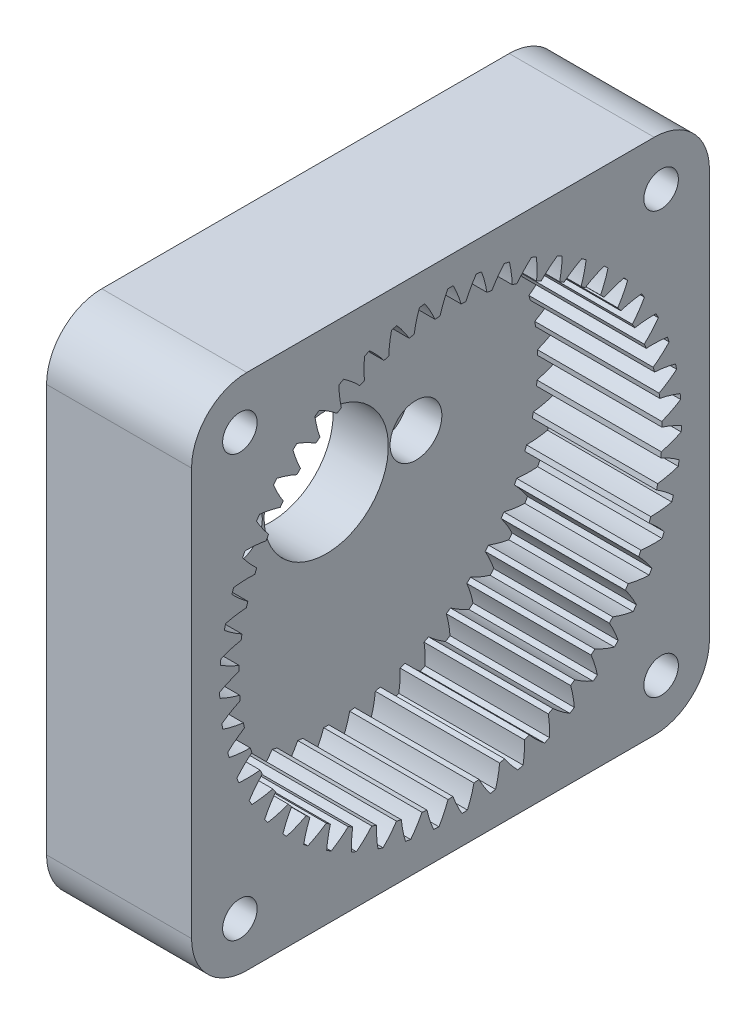
SolidWorks part; units mm, degrees
ref_plane "Plane1" through (0, 0, 0) normal (0, 0, 1) x (1, 0, 0)
ref_plane "Plane2" through (0, 0, 0) normal (0, 1, 0) x (1, 0, 0)
ref_plane "Plane3" through (0, 0, 0) normal (1, 0, 0) x (0, 0, -1)
sketch "HoldingSke" plane through (0, 0, 0) normal (0, 1, 0) x (1, 0, 0)
  line L0 (0, 0) -> (0.5035, -0.6217)
  line L1 (-15, 0) -> (100, 0) construction
  line L2 (0, 0) -> (-2.1039, 2.3779)
  line L3 (0, 0) -> (-11.863, 4.5341)
  line L4 (0, 0) -> (5.4348, 6.7114)
  line L5 (0, 0) -> (-23.7986, -8.8762)
  line L6 (0, 0) -> (-10.5278, -7.1032)
  line L7 (-2.1039, 2.3779) -> (3.3635, 27.1825)
  line L8 (-76.2, 3.6279) -> (-54.61, 3.6279)
  line L9 (-71.009, 38.7566) -> (-53.1078, 45.2721)
  line L10 (-76.2, 71.12) -> (104.1128, 71.12)
  line L11 (0, 0) -> (-12, 0)
  line L12 (-76.2, 101.6) -> (-76.155, 101.6)
  line L13 (24.9733, 27.94) -> (52.9518, 28.4284)
  line L14 (24.9733, 27.94) -> (24.9743, 27.94)
  line L15 (24.9733, 27.94) -> (100.4006, 29.5858)
  circle A0 centre (0, 0) radius 37.5
  circle A1 centre (0, 0) radius 12.7
  circle A2 centre (0, 0) radius 12.7
  dimension "MHD" = 25.4
  dimension "Hub_dia" = 25.4
  dimension "Diameter" = 75
  dimension "Num_teeth" = 51
  dimension "Pitch" = 0.8
  dimension "Overall_len" = 25.4
  dimension "Show_teeth" = 51
  dimension "Thickness" = 12.7
  dimension "OAL" = 25.4001
  dimension "T_dim" = 21.59
  dimension "Ap" = 20
  dimension "H" = 19.05
  dimension "Pitch_radius" = 180.3128
  dimension "Width" = 12
  dimension "Backlash" = 0.045
  dimension "Addendum_fac" = 1
  dimension "Dedendum_fac" = 1.25
  dimension "Clearance_fac" = 0.25
  dimension "Dedendum_add" = 0.001
  dimension "Module" = 1.25
sketch "BasProSke" plane through (0, 0, 0) normal (0, 1, 0) x (1, 0, 0)
  line L0 (-10, 0) -> (60, 0) construction
  line L1 (0, 30.625) -> (0, 37.5)
  line L2 (0, 30.625) -> (12, 30.625)
  line L3 (12, 30.625) -> (12, 37.5)
  line L4 (12, 37.5) -> (0, 37.5)
  dimension "Diameter" = 75
  dimension "Thickness" = 12
  dimension "Inside_diameter" = 61.25
revolve "Base-Revolve" add sketch "BasProSke" angle 360 about L0
sketch "TooCutSke" plane through (0, 0, 0) normal (1, 0, 0) x (0, 0, -1)
  line L3 (1.0941, 31.8562) -> (1.0941, 53.6633) construction
  line L4 (0, 0) -> (0, 59.563) construction
  line L5 (0, 0) -> (-4.2063, 68.1979) construction
  line L6 (-13.79, 26.1581) -> (36.1115, 29.2359) construction
  circle A0 centre (0, 0) radius 31.875 construction
  circle A1 centre (0, 0) radius 33.4385 construction
  circle A2 centre (0, 0) radius 26.9574 construction
  circle A3 centre (0, 0) radius 30.5996 construction
  arc A4 (1.5271, 30.5615) -> (0.3886, 33.4362) centre (-13.79, 26.1581) ccw
  arc A5 (1.5271, 30.5615) -> (-1.5271, 30.5615) centre (0, 0) ccw
  arc A6 (0.3886, 33.4362) -> (-0.3886, 33.4362) centre (0, 0) ccw
  arc A7 (-0.3886, 33.4362) -> (-1.5271, 30.5615) centre (13.79, 26.1581) ccw
  dimension "Pitch_dia" = 63.75
  dimension "Base_dia" = 53.9149
  dimension "Root_dia" = 66.877
  dimension "Overcut_dia" = 61.1992
  dimension "Flank_rad" = 15.9375
  dimension "Half_ang" = 3.529
  dimension "Half_CT" = 1.0941
extrude "ToothCut" cut sketch "TooCutSke" along normal through all
fillet "Breaks" [suppressed] radius 0.125
fillet "RootFillets" [suppressed] radius 0.3135
pattern_circular "TeethCuts" count 51 every 7.059 about axis through (-10, 0, 0) along (1, 0, 0) of "RootFillets", "Breaks", "ToothCut"
sketch "Sketch1" plane through (12, 0, 0) normal (1, 0, 0) x (0, 0, -1)
  line L1 (-37.5, 37.5) -> (37.5, 37.5)
  line L2 (-37.5, 37.5) -> (-37.5, -37.5)
  line L3 (-37.5, -37.5) -> (37.5, -37.5)
  line L4 (37.5, 37.5) -> (37.5, -37.5)
  circle A0 centre (0, 0) radius 37.5 construction
  circle A1 centre (0, 0) radius 37.5
extrude "Boss-Extrude1" add sketch "Sketch1" against normal up to surface (12 mm away) contours A1 L1 L2 | A1 L4 L1 | A1 L3 L4 | A1 L2 L3 up to face at (0, 0, 37.5)
sketch "Sketch2" plane through (0, 0, 0) normal (-1, 0, 0) x (0, 0, 1)
  line L1 (-37.5, 37.5) -> (37.5, 37.5)
  line L2 (-37.5, 37.5) -> (-37.5, -37.5)
  line L3 (-37.5, -37.5) -> (37.5, -37.5)
  line L4 (37.5, 37.5) -> (37.5, -37.5)
extrude "Boss-Extrude2" add sketch "Sketch2" along normal blind 3
sketch "Sketch3" plane through (-3, 0, 0) normal (-1, 0, 0) x (0, 0, 1)
  line L0 (0, 37.5) -> (0, -37.5)
  line L1 (37.5, 37.5) -> (-37.5, 37.5) construction
  line L2 (-37.5, -37.5) -> (37.5, -37.5) construction
  circle A0 centre (0, 0) radius 9
  dimension "D1" = 18
extrude "Cut-Extrude1" cut sketch "Sketch3" against normal through all contours L0 A0 | L0 A0
sketch "Sketch4" plane through (12, 0, 0) normal (1, 0, 0) x (0, 0, -1)
  line L1 (-37.5, 37.5) -> (37.5, 37.5)
  line L2 (-37.5, 37.5) -> (-37.5, -37.5)
  line L3 (-37.5, -37.5) -> (37.5, -37.5)
  line L4 (37.5, 37.5) -> (37.5, -37.5)
  arc A204 (3.7232, 33.2306) -> (2.2506, 30.5422) centre (16.9, 24.2652) ccw
  arc A205 (4.4946, 33.1351) -> (3.7232, 33.2306) centre (0, 0) ccw
  arc A206 (5.267, 30.1687) -> (4.4946, 33.1351) centre (-10.4709, 27.6545) ccw
  arc A207 (5.9868, 30.0341) -> (5.267, 30.1687) centre (0, 0) ccw
  arc A208 (7.7787, 32.5212) -> (5.9868, 30.0341) centre (19.7538, 22.0045) ccw
  arc A209 (8.5324, 32.3316) -> (7.7787, 32.5212) centre (0, 0) ccw
  arc A210 (8.9345, 29.2928) -> (8.5324, 32.3316) centre (-6.9932, 28.7316) ccw
  arc A211 (9.6323, 29.0708) -> (8.9345, 29.2928) centre (0, 0) ccw
  arc A212 (11.7162, 31.3188) -> (9.6323, 29.0708) centre (22.3082, 19.4102) ccw
  arc A213 (12.4409, 31.038) -> (11.7162, 31.3188) centre (0, 0) ccw
  arc A214 (12.4665, 27.9728) -> (12.4409, 31.038) centre (-3.4094, 29.3732) ccw
  arc A215 (13.1318, 27.6667) -> (12.4665, 27.9728) centre (0, 0) ccw
  arc A216 (15.4761, 29.6416) -> (13.1318, 27.6667) centre (24.5244, 16.5217) ccw
  arc A217 (16.1609, 29.2739) -> (15.4761, 29.6416) centre (0, 0) ccw
  arc A218 (15.8095, 26.2288) -> (16.1609, 29.2739) centre (0.2261, 29.5696) ccw
  arc A219 (16.4321, 25.8433) -> (15.8095, 26.2288) centre (0, 0) ccw
  arc A220 (19.0014, 27.5151) -> (16.4321, 25.8433) centre (26.3688, 13.3827) ccw
  arc A221 (19.6358, 27.066) -> (19.0014, 27.5151) centre (0, 0) ccw
  arc A222 (18.9129, 24.0872) -> (19.6358, 27.066) centre (3.8581, 29.3177) ccw
  arc A223 (19.4834, 23.6281) -> (18.9129, 24.0872) centre (0, 0) ccw
  arc A224 (22.2387, 24.9715) -> (19.4834, 23.6281) centre (27.8135, 10.0408) ccw
  arc A225 (22.813, 24.4479) -> (22.2387, 24.9715) centre (0, 0) ccw
  arc A226 (21.7296, 21.5804) -> (22.813, 24.4479) centre (7.4317, 28.6213) ccw
  arc A227 (22.2394, 21.0547) -> (21.7296, 21.5804) centre (0, 0) ccw
  arc A228 (25.1388, 22.0494) -> (22.2394, 21.0547) centre (28.8366, 6.5468) ccw
  arc A229 (25.6445, 21.4591) -> (25.1388, 22.0494) centre (0, 0) ccw
  arc A230 (24.2169, 18.7466) -> (25.6445, 21.4591) centre (10.8926, 27.4911) ccw
  arc A231 (24.6582, 18.1622) -> (24.2169, 18.7466) centre (0, 0) ccw
  arc A232 (27.6579, 18.793) -> (24.6582, 18.1622) centre (29.4226, 2.9535) ccw
  arc A233 (28.0872, 18.145) -> (27.6579, 18.793) centre (0, 0) ccw
  arc A234 (26.3371, 15.6285) -> (28.0872, 18.145) centre (14.1884, 25.9442) ccw
  arc A235 (26.7032, 14.9943) -> (26.3371, 15.6285) centre (0, 0) ccw
  arc A236 (29.7577, 15.2517) -> (26.7032, 14.9943) centre (29.5625, -0.6846) ccw
  arc A237 (30.1041, 14.5559) -> (29.7577, 15.2517) centre (0, 0) ccw
  arc A238 (28.058, 12.2735) -> (30.1041, 14.5559) centre (17.2691, 24.004) ccw
  arc A239 (28.3434, 11.5991) -> (28.058, 12.2735) centre (0, 0) ccw
  arc A240 (31.4064, 11.4792) -> (28.3434, 11.5991) centre (29.2543, -4.3123) ccw
  arc A241 (31.6647, 10.7462) -> (31.4064, 11.4792) centre (0, 0) ccw
  arc A242 (29.3536, 8.7325) -> (31.6647, 10.7462) centre (20.088, 21.6999) ccw
  arc A243 (29.554, 8.0282) -> (29.3536, 8.7325) centre (0, 0) ccw
  arc A244 (32.579, 7.5327) -> (29.554, 8.0282) centre (28.5027, -7.8746) ccw
  arc A245 (32.7453, 6.7735) -> (32.579, 7.5327) centre (0, 0) ccw
  arc A246 (30.2042, 5.0591) -> (32.7453, 6.7735) centre (22.6024, 19.0668) ccw
  arc A247 (30.3166, 4.3355) -> (30.2042, 5.0591) centre (0, 0) ccw
  arc A248 (33.2578, 3.4721) -> (30.3166, 4.3355) centre (27.3189, -11.3176) ccw
  arc A249 (33.3295, 2.6981) -> (33.2578, 3.4721) centre (0, 0) ccw
  arc A250 (30.597, 1.309) -> (33.3295, 2.6981) centre (24.7742, 16.1447) ccw
  arc A251 (30.6196, 0.5771) -> (30.597, 1.309) centre (0, 0) ccw
  arc A252 (33.4324, -0.6412) -> (30.6196, 0.5771) centre (25.7211, -14.589) ccw
  arc A253 (33.4084, -1.4181) -> (33.4324, -0.6412) centre (0, 0) ccw
  arc A254 (30.526, -2.4609) -> (33.4084, -1.4181) centre (26.5704, 12.9779) ccw
  arc A255 (30.4584, -3.1901) -> (30.526, -2.4609) centre (0, 0) ccw
  arc A256 (33.1002, -4.7448) -> (30.4584, -3.1901) centre (23.7333, -17.6392) ccw
  arc A257 (32.9809, -5.5129) -> (33.1002, -4.7448) centre (0, 0) ccw
  arc A258 (29.9922, -6.1936) -> (32.9809, -5.5129) centre (27.9638, 9.6143) ccw
  arc A259 (29.8355, -6.9089) -> (29.9922, -6.1936) centre (0, 0) ccw
  arc A260 (32.2662, -8.7765) -> (29.8355, -6.9089) centre (21.3857, -20.4221) ccw
  arc A261 (32.0535, -9.5241) -> (32.2662, -8.7765) centre (0, 0) ccw
  arc A262 (29.0037, -9.8323) -> (32.0535, -9.5241) centre (28.9334, 6.105) ccw
  arc A263 (28.7603, -10.523) -> (29.0037, -9.8323) centre (0, 0) ccw
  arc A264 (30.9431, -12.6751) -> (28.7603, -10.523) centre (18.714, -22.8953) ccw
  arc A265 (30.6401, -13.3909) -> (30.9431, -12.6751) centre (0, 0) ccw
  arc A266 (27.5756, -13.322) -> (30.6401, -13.3909) centre (29.4643, 2.5032) ccw
  arc A267 (27.2492, -13.9775) -> (27.5756, -13.322) centre (0, 0) ccw
  arc A268 (29.1509, -16.3816) -> (27.2492, -13.9775) centre (15.7586, -25.0215) ccw
  arc A269 (28.7623, -17.0547) -> (29.1509, -16.3816) centre (0, 0) ccw
  arc A270 (25.7295, -16.6097) -> (28.7623, -17.0547) centre (29.5486, -1.1366) ccw
  arc A271 (25.325, -17.2202) -> (25.7295, -16.6097) centre (0, 0) ccw
  arc A272 (26.9169, -19.8397) -> (25.325, -17.2202) centre (12.5643, -26.7684) ccw
  arc A273 (26.4485, -20.46) -> (26.9169, -19.8397) centre (0, 0) ccw
  arc A274 (23.4933, -19.6457) -> (26.4485, -20.46) centre (29.185, -4.7591) ccw
  arc A275 (23.0169, -20.2018) -> (23.4933, -19.6457) centre (0, 0) ccw
  arc A276 (24.2748, -22.9971) -> (23.0169, -20.2018) centre (9.1796, -28.1095) ccw
  arc A277 (23.7337, -23.5551) -> (24.2748, -22.9971) centre (0, 0) ccw
  arc A278 (20.901, -22.3839) -> (23.7337, -23.5551) centre (28.3789, -8.3096) ccw
  arc A279 (20.3599, -22.8772) -> (20.901, -22.3839) centre (0, 0) ccw
  arc A280 (21.2647, -25.8059) -> (20.3599, -22.8772) centre (5.6556, -29.0246) ccw
  arc A281 (20.6592, -26.2932) -> (21.2647, -25.8059) centre (0, 0) ccw
  arc A282 (17.9919, -24.7827) -> (20.6592, -26.2932) centre (27.1427, -11.734) ccw
  arc A283 (17.3942, -25.2058) -> (17.9919, -24.7827) centre (0, 0) ccw
  arc A284 (17.9323, -28.2235) -> (17.3942, -25.2058) centre (2.046, -29.4996) ccw
  arc A285 (17.2715, -28.6327) -> (17.9323, -28.2235) centre (0, 0) ccw
  arc A286 (14.81, -26.8058) -> (17.2715, -28.6327) centre (25.495, -14.9806) ccw
  arc A287 (14.1649, -27.1523) -> (14.81, -26.8058) centre (0, 0) ccw
  arc A288 (14.3281, -30.2132) -> (14.1649, -27.1523) centre (-1.5947, -29.5274) ccw
  arc A289 (13.622, -30.5381) -> (14.3281, -30.2132) centre (0, 0) ccw
  arc A290 (11.4037, -28.4227) -> (13.622, -30.5381) centre (23.4608, -18.0001) ccw
  arc A291 (10.7208, -28.6872) -> (11.4037, -28.4227) centre (0, 0) ccw
  arc A292 (10.5066, -31.745) -> (10.7208, -28.6872) centre (-5.2111, -29.1076) ccw
  arc A293 (9.7659, -31.9806) -> (10.5066, -31.745) centre (0, 0) ccw
  arc A294 (7.8244, -29.6086) -> (9.7659, -31.9806) centre (21.071, -20.7467) ccw
  arc A295 (7.1142, -29.7872) -> (7.8244, -29.6086) centre (0, 0) ccw
  arc A296 (6.5259, -32.7955) -> (7.1142, -29.7872) centre (-8.7486, -28.2466) ccw
  arc A297 (5.7619, -32.9383) -> (6.5259, -32.7955) centre (0, 0) ccw
  arc A298 (4.1266, -30.3457) -> (5.7619, -32.9383) centre (18.3617, -23.1788) ccw
  arc A299 (3.3998, -30.4357) -> (4.1266, -30.3457) centre (0, 0) ccw
  arc A300 (2.4463, -33.3489) -> (3.3998, -30.4357) centre (-12.1535, -26.9574) ccw
  arc A301 (1.6705, -33.3967) -> (2.4463, -33.3489) centre (0, 0) ccw
  arc A302 (0.3662, -30.6228) -> (1.6705, -33.3967) centre (15.3741, -25.2596) ccw
  arc A303 (-0.3662, -30.6228) -> (0.3662, -30.6228) centre (0, 0) ccw
  arc A304 (-1.6705, -33.3967) -> (-0.3662, -30.6228) centre (-15.3741, -25.2596) ccw
  arc A305 (-2.4463, -33.3489) -> (-1.6705, -33.3967) centre (0, 0) ccw
  arc A306 (-3.3998, -30.4357) -> (-2.4463, -33.3489) centre (12.1535, -26.9574) ccw
  arc A307 (-4.1266, -30.3457) -> (-3.3998, -30.4357) centre (0, 0) ccw
  arc A308 (-5.7619, -32.9383) -> (-4.1266, -30.3457) centre (-18.3617, -23.1788) ccw
  arc A309 (-6.5259, -32.7955) -> (-5.7619, -32.9383) centre (0, 0) ccw
  arc A310 (-7.1142, -29.7872) -> (-6.5259, -32.7955) centre (8.7486, -28.2466) ccw
  arc A311 (-7.8244, -29.6086) -> (-7.1142, -29.7872) centre (0, 0) ccw
  arc A312 (-9.7659, -31.9806) -> (-7.8244, -29.6086) centre (-21.071, -20.7467) ccw
  arc A313 (-10.5066, -31.745) -> (-9.7659, -31.9806) centre (0, 0) ccw
  arc A314 (-10.7208, -28.6872) -> (-10.5066, -31.745) centre (5.2111, -29.1076) ccw
  arc A315 (-11.4037, -28.4227) -> (-10.7208, -28.6872) centre (0, 0) ccw
  arc A316 (-13.622, -30.5381) -> (-11.4037, -28.4227) centre (-23.4608, -18.0001) ccw
  arc A317 (-14.3281, -30.2132) -> (-13.622, -30.5381) centre (0, 0) ccw
  arc A318 (-14.1649, -27.1523) -> (-14.3281, -30.2132) centre (1.5947, -29.5274) ccw
  arc A319 (-14.81, -26.8058) -> (-14.1649, -27.1523) centre (0, 0) ccw
  arc A320 (-17.2715, -28.6327) -> (-14.81, -26.8058) centre (-25.495, -14.9806) ccw
  arc A321 (-17.9323, -28.2235) -> (-17.2715, -28.6327) centre (0, 0) ccw
  arc A322 (-17.3942, -25.2058) -> (-17.9323, -28.2235) centre (-2.046, -29.4996) ccw
  arc A323 (-17.9919, -24.7827) -> (-17.3942, -25.2058) centre (0, 0) ccw
  arc A324 (-20.6592, -26.2932) -> (-17.9919, -24.7827) centre (-27.1427, -11.734) ccw
  arc A325 (-21.2647, -25.8059) -> (-20.6592, -26.2932) centre (0, 0) ccw
  arc A326 (-20.3599, -22.8772) -> (-21.2647, -25.8059) centre (-5.6556, -29.0246) ccw
  arc A327 (-20.901, -22.3839) -> (-20.3599, -22.8772) centre (0, 0) ccw
  arc A328 (-23.7337, -23.5551) -> (-20.901, -22.3839) centre (-28.3789, -8.3096) ccw
  arc A329 (-24.2748, -22.9971) -> (-23.7337, -23.5551) centre (0, 0) ccw
  arc A330 (-23.0169, -20.2018) -> (-24.2748, -22.9971) centre (-9.1796, -28.1095) ccw
  arc A331 (-23.4933, -19.6457) -> (-23.0169, -20.2018) centre (0, 0) ccw
  arc A332 (-26.4485, -20.46) -> (-23.4933, -19.6457) centre (-29.185, -4.7591) ccw
  arc A333 (-26.9169, -19.8397) -> (-26.4485, -20.46) centre (0, 0) ccw
  arc A334 (-25.325, -17.2202) -> (-26.9169, -19.8397) centre (-12.5643, -26.7684) ccw
  arc A335 (-25.7295, -16.6097) -> (-25.325, -17.2202) centre (0, 0) ccw
  arc A336 (-28.7623, -17.0547) -> (-25.7295, -16.6097) centre (-29.5486, -1.1366) ccw
  arc A337 (-29.1509, -16.3816) -> (-28.7623, -17.0547) centre (0, 0) ccw
  arc A338 (-27.2492, -13.9775) -> (-29.1509, -16.3816) centre (-15.7586, -25.0215) ccw
  arc A339 (-27.5756, -13.322) -> (-27.2492, -13.9775) centre (0, 0) ccw
  arc A340 (-30.6401, -13.3909) -> (-27.5756, -13.322) centre (-29.4643, 2.5032) ccw
  arc A341 (-30.9431, -12.6751) -> (-30.6401, -13.3909) centre (0, 0) ccw
  arc A342 (-28.7603, -10.523) -> (-30.9431, -12.6751) centre (-18.714, -22.8953) ccw
  arc A343 (-29.0037, -9.8323) -> (-28.7603, -10.523) centre (0, 0) ccw
  arc A344 (-32.0535, -9.5241) -> (-29.0037, -9.8323) centre (-28.9334, 6.105) ccw
  arc A345 (-32.2662, -8.7765) -> (-32.0535, -9.5241) centre (0, 0) ccw
  arc A346 (-29.8355, -6.9089) -> (-32.2662, -8.7765) centre (-21.3857, -20.4221) ccw
  arc A347 (-29.9922, -6.1936) -> (-29.8355, -6.9089) centre (0, 0) ccw
  arc A348 (-32.9809, -5.5129) -> (-29.9922, -6.1936) centre (-27.9638, 9.6143) ccw
  arc A349 (-33.1002, -4.7448) -> (-32.9809, -5.5129) centre (0, 0) ccw
  arc A350 (-30.4584, -3.1901) -> (-33.1002, -4.7448) centre (-23.7333, -17.6392) ccw
  arc A351 (-30.526, -2.4609) -> (-30.4584, -3.1901) centre (0, 0) ccw
  arc A352 (-33.4084, -1.4181) -> (-30.526, -2.4609) centre (-26.5704, 12.9779) ccw
  arc A353 (-33.4324, -0.6412) -> (-33.4084, -1.4181) centre (0, 0) ccw
  arc A354 (-30.6196, 0.5771) -> (-33.4324, -0.6412) centre (-25.7211, -14.589) ccw
  arc A355 (-30.597, 1.309) -> (-30.6196, 0.5771) centre (0, 0) ccw
  arc A356 (-33.3295, 2.6981) -> (-30.597, 1.309) centre (-24.7742, 16.1447) ccw
  arc A357 (-33.2578, 3.4721) -> (-33.3295, 2.6981) centre (0, 0) ccw
  arc A358 (-30.3166, 4.3355) -> (-33.2578, 3.4721) centre (-27.3189, -11.3176) ccw
  arc A359 (-30.2042, 5.0591) -> (-30.3166, 4.3355) centre (0, 0) ccw
  arc A360 (-32.7453, 6.7735) -> (-30.2042, 5.0591) centre (-22.6024, 19.0668) ccw
  arc A361 (-32.579, 7.5327) -> (-32.7453, 6.7735) centre (0, 0) ccw
  arc A362 (-29.554, 8.0282) -> (-32.579, 7.5327) centre (-28.5027, -7.8746) ccw
  arc A363 (-29.3536, 8.7325) -> (-29.554, 8.0282) centre (0, 0) ccw
  arc A364 (-31.6647, 10.7462) -> (-29.3536, 8.7325) centre (-20.088, 21.6999) ccw
  arc A365 (-31.4064, 11.4792) -> (-31.6647, 10.7462) centre (0, 0) ccw
  arc A366 (-28.3434, 11.5991) -> (-31.4064, 11.4792) centre (-29.2543, -4.3123) ccw
  arc A367 (-28.058, 12.2735) -> (-28.3434, 11.5991) centre (0, 0) ccw
  arc A368 (-30.1041, 14.5559) -> (-28.058, 12.2735) centre (-17.2691, 24.004) ccw
  arc A369 (-29.7577, 15.2517) -> (-30.1041, 14.5559) centre (0, 0) ccw
  arc A370 (-26.7032, 14.9943) -> (-29.7577, 15.2517) centre (-29.5625, -0.6846) ccw
  arc A371 (-26.3371, 15.6285) -> (-26.7032, 14.9943) centre (0, 0) ccw
  arc A372 (-28.0872, 18.145) -> (-26.3371, 15.6285) centre (-14.1884, 25.9442) ccw
  arc A373 (-27.6579, 18.793) -> (-28.0872, 18.145) centre (0, 0) ccw
  arc A374 (-24.6582, 18.1622) -> (-27.6579, 18.793) centre (-29.4226, 2.9535) ccw
  arc A375 (-24.2169, 18.7466) -> (-24.6582, 18.1622) centre (0, 0) ccw
  arc A376 (-25.6445, 21.4591) -> (-24.2169, 18.7466) centre (-10.8926, 27.4911) ccw
  arc A377 (-25.1388, 22.0494) -> (-25.6445, 21.4591) centre (0, 0) ccw
  arc A378 (-22.2394, 21.0547) -> (-25.1388, 22.0494) centre (-28.8366, 6.5468) ccw
  arc A379 (-21.7296, 21.5804) -> (-22.2394, 21.0547) centre (0, 0) ccw
  arc A380 (-22.813, 24.4479) -> (-21.7296, 21.5804) centre (-7.4317, 28.6213) ccw
  arc A381 (-22.2387, 24.9715) -> (-22.813, 24.4479) centre (0, 0) ccw
  arc A382 (-19.4834, 23.6281) -> (-22.2387, 24.9715) centre (-27.8135, 10.0408) ccw
  arc A383 (-18.9129, 24.0872) -> (-19.4834, 23.6281) centre (0, 0) ccw
  arc A384 (-19.6358, 27.066) -> (-18.9129, 24.0872) centre (-3.8581, 29.3177) ccw
  arc A385 (-19.0014, 27.5151) -> (-19.6358, 27.066) centre (0, 0) ccw
  arc A386 (-16.4321, 25.8433) -> (-19.0014, 27.5151) centre (-26.3688, 13.3827) ccw
  arc A387 (-15.8095, 26.2288) -> (-16.4321, 25.8433) centre (0, 0) ccw
  arc A388 (-16.1609, 29.2739) -> (-15.8095, 26.2288) centre (-0.2261, 29.5696) ccw
  arc A389 (-15.4761, 29.6416) -> (-16.1609, 29.2739) centre (0, 0) ccw
  arc A390 (-13.1318, 27.6667) -> (-15.4761, 29.6416) centre (-24.5244, 16.5217) ccw
  arc A391 (-12.4665, 27.9728) -> (-13.1318, 27.6667) centre (0, 0) ccw
  arc A392 (-12.4409, 31.038) -> (-12.4665, 27.9728) centre (3.4094, 29.3732) ccw
  arc A393 (-11.7162, 31.3188) -> (-12.4409, 31.038) centre (0, 0) ccw
  arc A394 (-9.6323, 29.0708) -> (-11.7162, 31.3188) centre (-22.3082, 19.4102) ccw
  arc A395 (-8.9345, 29.2928) -> (-9.6323, 29.0708) centre (0, 0) ccw
  arc A396 (-8.5324, 32.3316) -> (-8.9345, 29.2928) centre (6.9932, 28.7316) ccw
  arc A397 (-7.7787, 32.5212) -> (-8.5324, 32.3316) centre (0, 0) ccw
  arc A398 (-5.9868, 30.0341) -> (-7.7787, 32.5212) centre (-19.7538, 22.0045) ccw
  arc A399 (-5.267, 30.1687) -> (-5.9868, 30.0341) centre (0, 0) ccw
  arc A400 (-4.4946, 33.1351) -> (-5.267, 30.1687) centre (10.4709, 27.6545) ccw
  arc A401 (-3.7232, 33.2306) -> (-4.4946, 33.1351) centre (0, 0) ccw
  arc A402 (-2.2506, 30.5422) -> (-3.7232, 33.2306) centre (-16.9, 24.2652) ccw
  arc A403 (-1.5197, 30.5873) -> (-2.2506, 30.5422) centre (0, 0) ccw
  arc A404 (-0.3886, 33.4362) -> (-1.5197, 30.5873) centre (13.79, 26.1581) ccw
  arc A405 (0.3886, 33.4362) -> (-0.3886, 33.4362) centre (0, 0) ccw
  arc A406 (1.5197, 30.5873) -> (0.3886, 33.4362) centre (-13.79, 26.1581) ccw
  arc A407 (2.2506, 30.5422) -> (1.5197, 30.5873) centre (0, 0) ccw
  arc A408 (3.7232, 33.2306) -> (2.2506, 30.5422) centre (16.9, 24.2652) ccw
  arc A409 (4.4946, 33.1351) -> (3.7232, 33.2306) centre (0, 0) ccw
  arc A410 (5.267, 30.1687) -> (4.4946, 33.1351) centre (-10.4709, 27.6545) ccw
  arc A411 (5.9868, 30.0341) -> (5.267, 30.1687) centre (0, 0) ccw
  arc A412 (7.7787, 32.5212) -> (5.9868, 30.0341) centre (19.7538, 22.0045) ccw
  arc A413 (8.5324, 32.3316) -> (7.7787, 32.5212) centre (0, 0) ccw
  arc A414 (8.9345, 29.2928) -> (8.5324, 32.3316) centre (-6.9932, 28.7316) ccw
  arc A415 (9.6323, 29.0708) -> (8.9345, 29.2928) centre (0, 0) ccw
  arc A416 (11.7162, 31.3188) -> (9.6323, 29.0708) centre (22.3082, 19.4102) ccw
  arc A417 (12.4409, 31.038) -> (11.7162, 31.3188) centre (0, 0) ccw
  arc A418 (12.4665, 27.9728) -> (12.4409, 31.038) centre (-3.4094, 29.3732) ccw
  arc A419 (13.1318, 27.6667) -> (12.4665, 27.9728) centre (0, 0) ccw
  arc A420 (15.4761, 29.6416) -> (13.1318, 27.6667) centre (24.5244, 16.5217) ccw
  arc A421 (16.1609, 29.2739) -> (15.4761, 29.6416) centre (0, 0) ccw
  arc A422 (15.8095, 26.2288) -> (16.1609, 29.2739) centre (0.2261, 29.5696) ccw
  arc A423 (16.4321, 25.8433) -> (15.8095, 26.2288) centre (0, 0) ccw
  arc A424 (19.0014, 27.5151) -> (16.4321, 25.8433) centre (26.3688, 13.3827) ccw
  arc A425 (19.6358, 27.066) -> (19.0014, 27.5151) centre (0, 0) ccw
  arc A426 (18.9129, 24.0872) -> (19.6358, 27.066) centre (3.8581, 29.3177) ccw
  arc A427 (19.4834, 23.6281) -> (18.9129, 24.0872) centre (0, 0) ccw
  arc A428 (22.2387, 24.9715) -> (19.4834, 23.6281) centre (27.8135, 10.0408) ccw
  arc A429 (22.813, 24.4479) -> (22.2387, 24.9715) centre (0, 0) ccw
  arc A430 (21.7296, 21.5804) -> (22.813, 24.4479) centre (7.4317, 28.6213) ccw
  arc A431 (22.2394, 21.0547) -> (21.7296, 21.5804) centre (0, 0) ccw
  arc A432 (25.1388, 22.0494) -> (22.2394, 21.0547) centre (28.8366, 6.5468) ccw
  arc A433 (25.6445, 21.4591) -> (25.1388, 22.0494) centre (0, 0) ccw
  arc A434 (24.2169, 18.7466) -> (25.6445, 21.4591) centre (10.8926, 27.4911) ccw
  arc A435 (24.6582, 18.1622) -> (24.2169, 18.7466) centre (0, 0) ccw
  arc A436 (27.6579, 18.793) -> (24.6582, 18.1622) centre (29.4226, 2.9535) ccw
  arc A437 (28.0872, 18.145) -> (27.6579, 18.793) centre (0, 0) ccw
  arc A438 (26.3371, 15.6285) -> (28.0872, 18.145) centre (14.1884, 25.9442) ccw
  arc A439 (26.7032, 14.9943) -> (26.3371, 15.6285) centre (0, 0) ccw
  arc A440 (29.7577, 15.2517) -> (26.7032, 14.9943) centre (29.5625, -0.6846) ccw
  arc A441 (30.1041, 14.5559) -> (29.7577, 15.2517) centre (0, 0) ccw
  arc A442 (28.058, 12.2735) -> (30.1041, 14.5559) centre (17.2691, 24.004) ccw
  arc A443 (28.3434, 11.5991) -> (28.058, 12.2735) centre (0, 0) ccw
  arc A444 (31.4064, 11.4792) -> (28.3434, 11.5991) centre (29.2543, -4.3123) ccw
  arc A445 (31.6647, 10.7462) -> (31.4064, 11.4792) centre (0, 0) ccw
  arc A446 (29.3536, 8.7325) -> (31.6647, 10.7462) centre (20.088, 21.6999) ccw
  arc A447 (29.554, 8.0282) -> (29.3536, 8.7325) centre (0, 0) ccw
  arc A448 (32.579, 7.5327) -> (29.554, 8.0282) centre (28.5027, -7.8746) ccw
  arc A449 (32.7453, 6.7735) -> (32.579, 7.5327) centre (0, 0) ccw
  arc A450 (30.2042, 5.0591) -> (32.7453, 6.7735) centre (22.6024, 19.0668) ccw
  arc A451 (30.3166, 4.3355) -> (30.2042, 5.0591) centre (0, 0) ccw
  arc A452 (33.2578, 3.4721) -> (30.3166, 4.3355) centre (27.3189, -11.3176) ccw
  arc A453 (33.3295, 2.6981) -> (33.2578, 3.4721) centre (0, 0) ccw
  arc A454 (30.597, 1.309) -> (33.3295, 2.6981) centre (24.7742, 16.1447) ccw
  arc A455 (30.6196, 0.5771) -> (30.597, 1.309) centre (0, 0) ccw
  arc A456 (33.4324, -0.6412) -> (30.6196, 0.5771) centre (25.7211, -14.589) ccw
  arc A457 (33.4084, -1.4181) -> (33.4324, -0.6412) centre (0, 0) ccw
  arc A458 (30.526, -2.4609) -> (33.4084, -1.4181) centre (26.5704, 12.9779) ccw
  arc A459 (30.4584, -3.1901) -> (30.526, -2.4609) centre (0, 0) ccw
  arc A460 (33.1002, -4.7448) -> (30.4584, -3.1901) centre (23.7333, -17.6392) ccw
  arc A461 (32.9809, -5.5129) -> (33.1002, -4.7448) centre (0, 0) ccw
  arc A462 (29.9922, -6.1936) -> (32.9809, -5.5129) centre (27.9638, 9.6143) ccw
  arc A463 (29.8355, -6.9089) -> (29.9922, -6.1936) centre (0, 0) ccw
  arc A464 (32.2662, -8.7765) -> (29.8355, -6.9089) centre (21.3857, -20.4221) ccw
  arc A465 (32.0535, -9.5241) -> (32.2662, -8.7765) centre (0, 0) ccw
  arc A466 (29.0037, -9.8323) -> (32.0535, -9.5241) centre (28.9334, 6.105) ccw
  arc A467 (28.7603, -10.523) -> (29.0037, -9.8323) centre (0, 0) ccw
  arc A468 (30.9431, -12.6751) -> (28.7603, -10.523) centre (18.714, -22.8953) ccw
  arc A469 (30.6401, -13.3909) -> (30.9431, -12.6751) centre (0, 0) ccw
  arc A470 (27.5756, -13.322) -> (30.6401, -13.3909) centre (29.4643, 2.5032) ccw
  arc A471 (27.2492, -13.9775) -> (27.5756, -13.322) centre (0, 0) ccw
  arc A472 (29.1509, -16.3816) -> (27.2492, -13.9775) centre (15.7586, -25.0215) ccw
  arc A473 (28.7623, -17.0547) -> (29.1509, -16.3816) centre (0, 0) ccw
  arc A474 (25.7295, -16.6097) -> (28.7623, -17.0547) centre (29.5486, -1.1366) ccw
  arc A475 (25.325, -17.2202) -> (25.7295, -16.6097) centre (0, 0) ccw
  arc A476 (26.9169, -19.8397) -> (25.325, -17.2202) centre (12.5643, -26.7684) ccw
  arc A477 (26.4485, -20.46) -> (26.9169, -19.8397) centre (0, 0) ccw
  arc A478 (23.4933, -19.6457) -> (26.4485, -20.46) centre (29.185, -4.7591) ccw
  arc A479 (23.0169, -20.2018) -> (23.4933, -19.6457) centre (0, 0) ccw
  arc A480 (24.2748, -22.9971) -> (23.0169, -20.2018) centre (9.1796, -28.1095) ccw
  arc A481 (23.7337, -23.5551) -> (24.2748, -22.9971) centre (0, 0) ccw
  arc A482 (20.901, -22.3839) -> (23.7337, -23.5551) centre (28.3789, -8.3096) ccw
  arc A483 (20.3599, -22.8772) -> (20.901, -22.3839) centre (0, 0) ccw
  arc A484 (21.2647, -25.8059) -> (20.3599, -22.8772) centre (5.6556, -29.0246) ccw
  arc A485 (20.6592, -26.2932) -> (21.2647, -25.8059) centre (0, 0) ccw
  arc A486 (17.9919, -24.7827) -> (20.6592, -26.2932) centre (27.1427, -11.734) ccw
  arc A487 (17.3942, -25.2058) -> (17.9919, -24.7827) centre (0, 0) ccw
  arc A488 (17.9323, -28.2235) -> (17.3942, -25.2058) centre (2.046, -29.4996) ccw
  arc A489 (17.2715, -28.6327) -> (17.9323, -28.2235) centre (0, 0) ccw
  arc A490 (14.81, -26.8058) -> (17.2715, -28.6327) centre (25.495, -14.9806) ccw
  arc A491 (14.1649, -27.1523) -> (14.81, -26.8058) centre (0, 0) ccw
  arc A492 (14.3281, -30.2132) -> (14.1649, -27.1523) centre (-1.5947, -29.5274) ccw
  arc A493 (13.622, -30.5381) -> (14.3281, -30.2132) centre (0, 0) ccw
  arc A494 (11.4037, -28.4227) -> (13.622, -30.5381) centre (23.4608, -18.0001) ccw
  arc A495 (10.7208, -28.6872) -> (11.4037, -28.4227) centre (0, 0) ccw
  arc A496 (10.5066, -31.745) -> (10.7208, -28.6872) centre (-5.2111, -29.1076) ccw
  arc A497 (9.7659, -31.9806) -> (10.5066, -31.745) centre (0, 0) ccw
  arc A498 (7.8244, -29.6086) -> (9.7659, -31.9806) centre (21.071, -20.7467) ccw
  arc A499 (7.1142, -29.7872) -> (7.8244, -29.6086) centre (0, 0) ccw
  arc A500 (6.5259, -32.7955) -> (7.1142, -29.7872) centre (-8.7486, -28.2466) ccw
  arc A501 (5.7619, -32.9383) -> (6.5259, -32.7955) centre (0, 0) ccw
  arc A502 (4.1266, -30.3457) -> (5.7619, -32.9383) centre (18.3617, -23.1788) ccw
  arc A503 (3.3998, -30.4357) -> (4.1266, -30.3457) centre (0, 0) ccw
  arc A504 (2.4463, -33.3489) -> (3.3998, -30.4357) centre (-12.1535, -26.9574) ccw
  arc A505 (1.6705, -33.3967) -> (2.4463, -33.3489) centre (0, 0) ccw
  arc A506 (0.3662, -30.6228) -> (1.6705, -33.3967) centre (15.3741, -25.2596) ccw
  arc A507 (-0.3662, -30.6228) -> (0.3662, -30.6228) centre (0, 0) ccw
  arc A508 (-1.6705, -33.3967) -> (-0.3662, -30.6228) centre (-15.3741, -25.2596) ccw
  arc A509 (-2.4463, -33.3489) -> (-1.6705, -33.3967) centre (0, 0) ccw
  arc A510 (-3.3998, -30.4357) -> (-2.4463, -33.3489) centre (12.1535, -26.9574) ccw
  arc A511 (-4.1266, -30.3457) -> (-3.3998, -30.4357) centre (0, 0) ccw
  arc A512 (-5.7619, -32.9383) -> (-4.1266, -30.3457) centre (-18.3617, -23.1788) ccw
  arc A513 (-6.5259, -32.7955) -> (-5.7619, -32.9383) centre (0, 0) ccw
  arc A514 (-7.1142, -29.7872) -> (-6.5259, -32.7955) centre (8.7486, -28.2466) ccw
  arc A515 (-7.8244, -29.6086) -> (-7.1142, -29.7872) centre (0, 0) ccw
  arc A516 (-9.7659, -31.9806) -> (-7.8244, -29.6086) centre (-21.071, -20.7467) ccw
  arc A517 (-10.5066, -31.745) -> (-9.7659, -31.9806) centre (0, 0) ccw
  arc A518 (-10.7208, -28.6872) -> (-10.5066, -31.745) centre (5.2111, -29.1076) ccw
  arc A519 (-11.4037, -28.4227) -> (-10.7208, -28.6872) centre (0, 0) ccw
  arc A520 (-13.622, -30.5381) -> (-11.4037, -28.4227) centre (-23.4608, -18.0001) ccw
  arc A521 (-14.3281, -30.2132) -> (-13.622, -30.5381) centre (0, 0) ccw
  arc A522 (-14.1649, -27.1523) -> (-14.3281, -30.2132) centre (1.5947, -29.5274) ccw
  arc A523 (-14.81, -26.8058) -> (-14.1649, -27.1523) centre (0, 0) ccw
  arc A524 (-17.2715, -28.6327) -> (-14.81, -26.8058) centre (-25.495, -14.9806) ccw
  arc A525 (-17.9323, -28.2235) -> (-17.2715, -28.6327) centre (0, 0) ccw
  arc A526 (-17.3942, -25.2058) -> (-17.9323, -28.2235) centre (-2.046, -29.4996) ccw
  arc A527 (-17.9919, -24.7827) -> (-17.3942, -25.2058) centre (0, 0) ccw
  arc A528 (-20.6592, -26.2932) -> (-17.9919, -24.7827) centre (-27.1427, -11.734) ccw
  arc A529 (-21.2647, -25.8059) -> (-20.6592, -26.2932) centre (0, 0) ccw
  arc A530 (-20.3599, -22.8772) -> (-21.2647, -25.8059) centre (-5.6556, -29.0246) ccw
  arc A531 (-20.901, -22.3839) -> (-20.3599, -22.8772) centre (0, 0) ccw
  arc A532 (-23.7337, -23.5551) -> (-20.901, -22.3839) centre (-28.3789, -8.3096) ccw
  arc A533 (-24.2748, -22.9971) -> (-23.7337, -23.5551) centre (0, 0) ccw
  arc A534 (-23.0169, -20.2018) -> (-24.2748, -22.9971) centre (-9.1796, -28.1095) ccw
  arc A535 (-23.4933, -19.6457) -> (-23.0169, -20.2018) centre (0, 0) ccw
  arc A536 (-26.4485, -20.46) -> (-23.4933, -19.6457) centre (-29.185, -4.7591) ccw
  arc A537 (-26.9169, -19.8397) -> (-26.4485, -20.46) centre (0, 0) ccw
  arc A538 (-25.325, -17.2202) -> (-26.9169, -19.8397) centre (-12.5643, -26.7684) ccw
  arc A539 (-25.7295, -16.6097) -> (-25.325, -17.2202) centre (0, 0) ccw
  arc A540 (-28.7623, -17.0547) -> (-25.7295, -16.6097) centre (-29.5486, -1.1366) ccw
  arc A541 (-29.1509, -16.3816) -> (-28.7623, -17.0547) centre (0, 0) ccw
  arc A542 (-27.2492, -13.9775) -> (-29.1509, -16.3816) centre (-15.7586, -25.0215) ccw
  arc A543 (-27.5756, -13.322) -> (-27.2492, -13.9775) centre (0, 0) ccw
  arc A544 (-30.6401, -13.3909) -> (-27.5756, -13.322) centre (-29.4643, 2.5032) ccw
  arc A545 (-30.9431, -12.6751) -> (-30.6401, -13.3909) centre (0, 0) ccw
  arc A546 (-28.7603, -10.523) -> (-30.9431, -12.6751) centre (-18.714, -22.8953) ccw
  arc A547 (-29.0037, -9.8323) -> (-28.7603, -10.523) centre (0, 0) ccw
  arc A548 (-32.0535, -9.5241) -> (-29.0037, -9.8323) centre (-28.9334, 6.105) ccw
  arc A549 (-32.2662, -8.7765) -> (-32.0535, -9.5241) centre (0, 0) ccw
  arc A550 (-29.8355, -6.9089) -> (-32.2662, -8.7765) centre (-21.3857, -20.4221) ccw
  arc A551 (-29.9922, -6.1936) -> (-29.8355, -6.9089) centre (0, 0) ccw
  arc A552 (-32.9809, -5.5129) -> (-29.9922, -6.1936) centre (-27.9638, 9.6143) ccw
  arc A553 (-33.1002, -4.7448) -> (-32.9809, -5.5129) centre (0, 0) ccw
  arc A554 (-30.4584, -3.1901) -> (-33.1002, -4.7448) centre (-23.7333, -17.6392) ccw
  arc A555 (-30.526, -2.4609) -> (-30.4584, -3.1901) centre (0, 0) ccw
  arc A556 (-33.4084, -1.4181) -> (-30.526, -2.4609) centre (-26.5704, 12.9779) ccw
  arc A557 (-33.4324, -0.6412) -> (-33.4084, -1.4181) centre (0, 0) ccw
  arc A558 (-30.6196, 0.5771) -> (-33.4324, -0.6412) centre (-25.7211, -14.589) ccw
  arc A559 (-30.597, 1.309) -> (-30.6196, 0.5771) centre (0, 0) ccw
  arc A560 (-33.3295, 2.6981) -> (-30.597, 1.309) centre (-24.7742, 16.1447) ccw
  arc A561 (-33.2578, 3.4721) -> (-33.3295, 2.6981) centre (0, 0) ccw
  arc A562 (-30.3166, 4.3355) -> (-33.2578, 3.4721) centre (-27.3189, -11.3176) ccw
  arc A563 (-30.2042, 5.0591) -> (-30.3166, 4.3355) centre (0, 0) ccw
  arc A564 (-32.7453, 6.7735) -> (-30.2042, 5.0591) centre (-22.6024, 19.0668) ccw
  arc A565 (-32.579, 7.5327) -> (-32.7453, 6.7735) centre (0, 0) ccw
  arc A566 (-29.554, 8.0282) -> (-32.579, 7.5327) centre (-28.5027, -7.8746) ccw
  arc A567 (-29.3536, 8.7325) -> (-29.554, 8.0282) centre (0, 0) ccw
  arc A568 (-31.6647, 10.7462) -> (-29.3536, 8.7325) centre (-20.088, 21.6999) ccw
  arc A569 (-31.4064, 11.4792) -> (-31.6647, 10.7462) centre (0, 0) ccw
  arc A570 (-28.3434, 11.5991) -> (-31.4064, 11.4792) centre (-29.2543, -4.3123) ccw
  arc A571 (-28.058, 12.2735) -> (-28.3434, 11.5991) centre (0, 0) ccw
  arc A572 (-30.1041, 14.5559) -> (-28.058, 12.2735) centre (-17.2691, 24.004) ccw
  arc A573 (-29.7577, 15.2517) -> (-30.1041, 14.5559) centre (0, 0) ccw
  arc A574 (-26.7032, 14.9943) -> (-29.7577, 15.2517) centre (-29.5625, -0.6846) ccw
  arc A575 (-26.3371, 15.6285) -> (-26.7032, 14.9943) centre (0, 0) ccw
  arc A576 (-28.0872, 18.145) -> (-26.3371, 15.6285) centre (-14.1884, 25.9442) ccw
  arc A577 (-27.6579, 18.793) -> (-28.0872, 18.145) centre (0, 0) ccw
  arc A578 (-24.6582, 18.1622) -> (-27.6579, 18.793) centre (-29.4226, 2.9535) ccw
  arc A579 (-24.2169, 18.7466) -> (-24.6582, 18.1622) centre (0, 0) ccw
  arc A580 (-25.6445, 21.4591) -> (-24.2169, 18.7466) centre (-10.8926, 27.4911) ccw
  arc A581 (-25.1388, 22.0494) -> (-25.6445, 21.4591) centre (0, 0) ccw
  arc A582 (-22.2394, 21.0547) -> (-25.1388, 22.0494) centre (-28.8366, 6.5468) ccw
  arc A583 (-21.7296, 21.5804) -> (-22.2394, 21.0547) centre (0, 0) ccw
  arc A584 (-22.813, 24.4479) -> (-21.7296, 21.5804) centre (-7.4317, 28.6213) ccw
  arc A585 (-22.2387, 24.9715) -> (-22.813, 24.4479) centre (0, 0) ccw
  arc A586 (-19.4834, 23.6281) -> (-22.2387, 24.9715) centre (-27.8135, 10.0408) ccw
  arc A587 (-18.9129, 24.0872) -> (-19.4834, 23.6281) centre (0, 0) ccw
  arc A588 (-19.6358, 27.066) -> (-18.9129, 24.0872) centre (-3.8581, 29.3177) ccw
  arc A589 (-19.0014, 27.5151) -> (-19.6358, 27.066) centre (0, 0) ccw
  arc A590 (-16.4321, 25.8433) -> (-19.0014, 27.5151) centre (-26.3688, 13.3827) ccw
  arc A591 (-15.8095, 26.2288) -> (-16.4321, 25.8433) centre (0, 0) ccw
  arc A592 (-16.1609, 29.2739) -> (-15.8095, 26.2288) centre (-0.2261, 29.5696) ccw
  arc A593 (-15.4761, 29.6416) -> (-16.1609, 29.2739) centre (0, 0) ccw
  arc A594 (-13.1318, 27.6667) -> (-15.4761, 29.6416) centre (-24.5244, 16.5217) ccw
  arc A595 (-12.4665, 27.9728) -> (-13.1318, 27.6667) centre (0, 0) ccw
  arc A596 (-12.4409, 31.038) -> (-12.4665, 27.9728) centre (3.4094, 29.3732) ccw
  arc A597 (-11.7162, 31.3188) -> (-12.4409, 31.038) centre (0, 0) ccw
  arc A598 (-9.6323, 29.0708) -> (-11.7162, 31.3188) centre (-22.3082, 19.4102) ccw
  arc A599 (-8.9345, 29.2928) -> (-9.6323, 29.0708) centre (0, 0) ccw
  arc A600 (-8.5324, 32.3316) -> (-8.9345, 29.2928) centre (6.9932, 28.7316) ccw
  arc A601 (-7.7787, 32.5212) -> (-8.5324, 32.3316) centre (0, 0) ccw
  arc A602 (-5.9868, 30.0341) -> (-7.7787, 32.5212) centre (-19.7538, 22.0045) ccw
  arc A603 (-5.267, 30.1687) -> (-5.9868, 30.0341) centre (0, 0) ccw
  arc A604 (-4.4946, 33.1351) -> (-5.267, 30.1687) centre (10.4709, 27.6545) ccw
  arc A605 (-3.7232, 33.2306) -> (-4.4946, 33.1351) centre (0, 0) ccw
  arc A606 (-2.2506, 30.5422) -> (-3.7232, 33.2306) centre (-16.9, 24.2652) ccw
  arc A607 (-1.5197, 30.5873) -> (-2.2506, 30.5422) centre (0, 0) ccw
  arc A608 (-0.3886, 33.4362) -> (-1.5197, 30.5873) centre (13.79, 26.1581) ccw
  arc A609 (0.3886, 33.4362) -> (-0.3886, 33.4362) centre (0, 0) ccw
  arc A610 (1.5197, 30.5873) -> (0.3886, 33.4362) centre (-13.79, 26.1581) ccw
  arc A611 (2.2506, 30.5422) -> (1.5197, 30.5873) centre (0, 0) ccw
  dimension "D1" = 0
extrude "Boss-Extrude3" add sketch "Sketch4" along normal blind 6
sketch "Sketch6" plane through (-3, 0, 0) normal (-1, 0, 0) x (0, 0, 1)
  line L0 (0, 0) -> (-13, 0) construction
  line L1 (0, 0) -> (13, 0) construction
  circle A0 centre (0, 0) radius 9 construction
  circle A1 centre (0, 0) radius 9
  circle A2 centre (0, 0) radius 20
  circle A3 centre (-13, 0) radius 2
  circle A4 centre (13, 0) radius 2
  dimension "D1" = 40
  dimension "D3" = 4
  dimension "D2" = 13
extrude "Boss-Extrude4" add sketch "Sketch6" along normal blind 5
sketch "Sketch7" plane through (-3, 0, 0) normal (-1, 0, 0) x (0, 0, 1)
  circle A0 centre (-13, 0) radius 2 construction
  circle A1 centre (13, 0) radius 2 construction
  circle A2 centre (-13, 0) radius 2
  circle A3 centre (13, 0) radius 2
extrude "Cut-Extrude2" cut sketch "Sketch7" against normal through all
sketch "Sketch8" plane through (0, 0, 0) normal (1, 0, 0) x (0, 0, -1)
  circle A0 centre (-13, 0) radius 3.75
  circle A1 centre (13, 0) radius 3.75
  dimension "D1" = 7.5
extrude "Cut-Extrude4" cut sketch "Sketch8" against normal blind 5
sketch "Sketch9" plane through (18, 0, 0) normal (1, 0, 0) x (0, 0, -1)
  line L0 (-30.5, 30.5) -> (-30.5, 37.5) construction
  line L1 (37.5, 37.5) -> (-37.5, 37.5) construction
  line L2 (-30.5, 30.5) -> (-37.5, 30.5) construction
  line L3 (-37.5, 37.5) -> (-37.5, -37.5) construction
  line L4 (0, 37.5) -> (0, -37.5) construction
  line L5 (-37.5, -37.5) -> (37.5, -37.5) construction
  line L6 (-37.5, 0) -> (37.5, 0) construction
  line L7 (37.5, -37.5) -> (37.5, 37.5) construction
  circle A0 centre (-30.5, 30.5) radius 2.5
  circle A1 centre (30.5, 30.5) radius 2.5
  circle A2 centre (30.5, -30.5) radius 2.5
  circle A3 centre (-30.5, -30.5) radius 2.5
  dimension "D1" = 7
  dimension "D2" = 5
extrude "Cut-Extrude5" cut sketch "Sketch9" against normal through all
fillet "Fillet1" radius 8 4 edges at (7.5, -37.5, 37.5) (7.5, -37.5, -37.5) (7.5, 37.5, -37.5) (7.5, 37.5, 37.5)
equation "' \"Module@HoldingSke\" = 6.35"
equation "' \"Num_teeth@HoldingSke\" = 24"
equation "' \"Ap@HoldingSke\" =  14.5"
equation "' \"Ap@HoldingSke\" = 14.5"
equation "' \"Width@HoldingSke\" = 12"
equation "' \"Diameter@HoldingSke\" = 8 * 25.4"
equation "' \"Show_teeth@HoldingSke\" = 100"
equation "' \"Backlash@HoldingSke\" = 0.009 * 25.4"
equation "' \"Addendum_fac@HoldingSke\" = 1.0"
equation "' \"Dedendum_fac@HoldingSke\" = 1.25"
equation "' \"Dedendum_add@HoldingSke\" = 0.00005 * 25.4"
equation "' \"Clearance_fac@HoldingSke\" = 0.25"
equation "\"Pitch@HoldingSke\" = 1 / \"Module@HoldingSke\" "
equation "\"Overcut_dia@TooCutSke\" = (\"Num_teeth@HoldingSke\" - 2 * \"Addendum_fac@HoldingSke\") / \"Pitch@HoldingSke\" - 0.002 * 25.4"
equation "\"Pitch_dia@TooCutSke\" = \"Num_teeth@HoldingSke\" / \"Pitch@HoldingSke\""
equation "\"Base_dia@TooCutSke\" = \"Num_teeth@HoldingSke\" / \"Pitch@HoldingSke\" * cos((\"Ap@HoldingSke\"  * 3.14159265 / 180)) * 0.90"
equation "\"Root_dia@TooCutSke\" = \"Num_teeth@HoldingSke\"  / \"Pitch@HoldingSke\" + 2 *  \"Dedendum_fac@HoldingSke\"/ \"Pitch@HoldingSke\" + \"Dedendum_add@HoldingSke\" * 2"
equation "\"Half_ang@TooCutSke\" = 180 / \"Num_teeth@HoldingSke\""
equation "\"Half_CT@TooCutSke\" = \"Num_teeth@HoldingSke\" / \"Pitch@HoldingSke\" * sin((3.14159265 / 2 / \"Num_teeth@HoldingSke\")) / 2 + 10 * \"Backlash@HoldingSke\" / 4"
equation "\"Flank_rad@TooCutSke\" = \"Num_teeth@HoldingSke\" / \"Pitch@HoldingSke\" / 4"
equation "\"Radius@RootFillets\"= \"Clearance_fac@HoldingSke\" / \"Pitch@HoldingSke\" + \"Dedendum_add@HoldingSke\""
equation "\"Break_rad@Breaks\" = 0.02 / \"Pitch@HoldingSke\" * 5"
equation "\"Num_teeth@TeethCuts\" = int( \"Show_teeth@HoldingSke\" ) + 1"
equation "\"Num_teeth@TeethCuts\" = ((sgn( \"Num_teeth@TeethCuts\" - \"Num_teeth@HoldingSke\" )-1)*( \"Num_teeth@TeethCuts\" - \"Num_teeth@HoldingSke\" ))/-2+ \"Num_teeth@HoldingSke\""
equation "\"Num_teeth@TeethCuts\" = ((sgn( \"Num_teeth@TeethCuts\" - 2.0)+1)*( \"Num_teeth@TeethCuts\" - 2.0))/2 +2.0"
equation "\"Angle@TeethCuts\" = 360.0 / \"Num_teeth@HoldingSke\""
equation "\"Diameter@BasProSke\" = \"Num_teeth@HoldingSke\"  / \"Pitch@HoldingSke\" + 2 *  \"Dedendum_fac@HoldingSke\"/ \"Pitch@HoldingSke\" + \"Dedendum_add@HoldingSke\" * 2 + 0.002 * 25.4"
equation "\"Diameter@BasProSke\" = ((sgn( \"Diameter@BasProSke\"  - \"Diameter@HoldingSke\" )+1)*( \"Diameter@BasProSke\"  - \"Diameter@HoldingSke\" ))/2 + \"Diameter@HoldingSke\""
equation "\"Inside_diameter@BasProSke\" =  (\"Num_teeth@HoldingSke\" - 2 * \"Addendum_fac@HoldingSke\") / \"Pitch@HoldingSke\" "
equation "\"Thickness@BasProSke\"  = \"Width@HoldingSke\""
